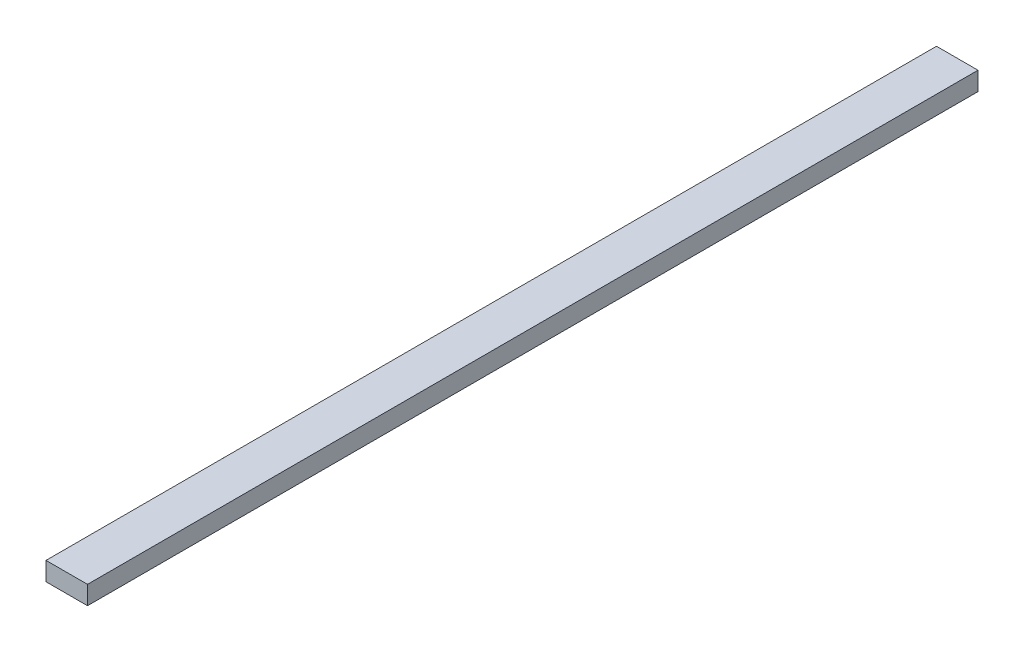
SolidWorks part; units mm, degrees
ref_plane "Front Plane" through (0, 0, 0) normal (1, 0, 0) x (0, 1, 0)
ref_plane "Top Plane" through (0, 0, 0) normal (0, 0, 1) x (0, 1, 0)
ref_plane "Right Plane" through (0, 0, 0) normal (0, 1, 0) x (-1, 0, 0)
sketch "Sketch1" plane through (0, 0, 0) normal (0, 0, 1) x (0, 1, 0)
  line L1 (-8.3312, -18.6436) -> (8.3312, -18.6436)
  line L2 (-8.3312, -18.6436) -> (-8.3312, 18.6436)
  line L3 (-8.3312, 18.6436) -> (8.3312, 18.6436)
  line L4 (8.3312, -18.6436) -> (8.3312, 18.6436)
  line L5 (-8.3312, -18.6436) -> (8.3312, 18.6436) construction
  line L6 (-8.3312, 18.6436) -> (8.3312, -18.6436) construction
  point P0 (0, 0)
  dimension "D1" = 16.6624
  dimension "D2" = 37.2872
extrude "Boss-Extrude1" add sketch "Sketch1" along normal mid plane 800
